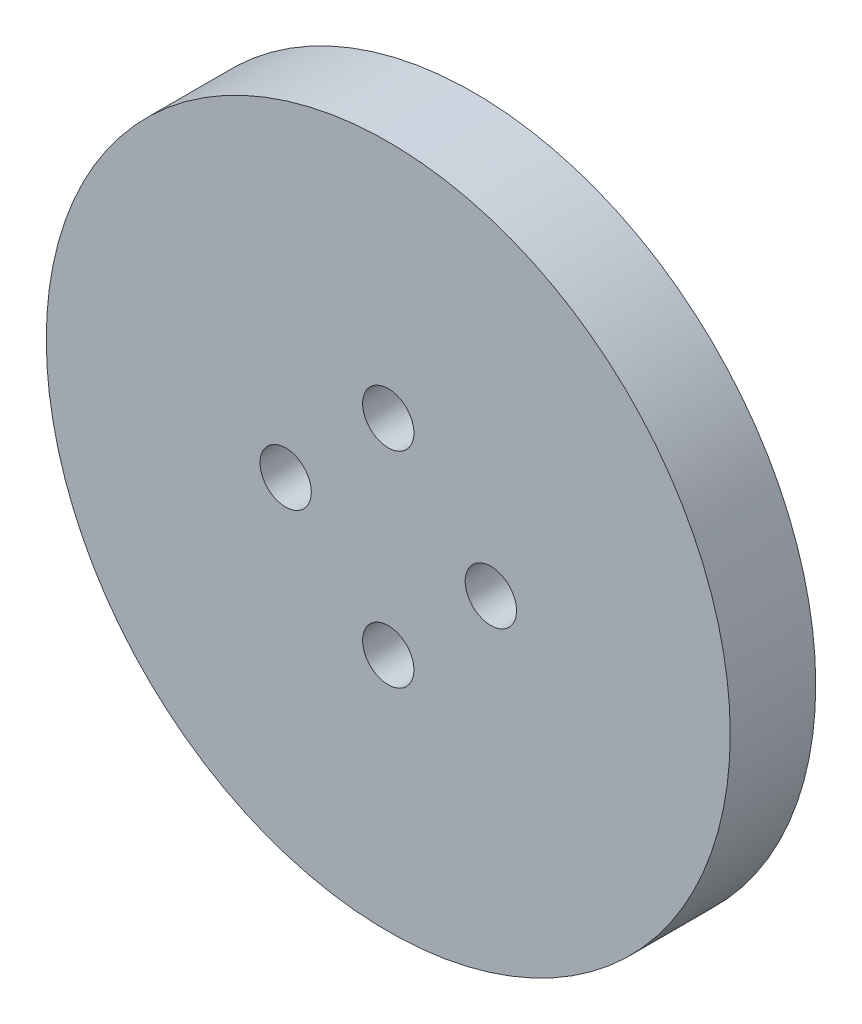
SolidWorks part; units mm, degrees
ref_plane "前视基准面" through (0, 0, 0) normal (0, 0, 1) x (1, 0, 0)
ref_plane "上视基准面" through (0, 0, 0) normal (0, 1, 0) x (1, 0, 0)
ref_plane "右视基准面" through (0, 0, 0) normal (1, 0, 0) x (0, 0, -1)
sketch "草图1" plane through (0, 0, 0) normal (0, 0, 1) x (1, 0, 0)
  circle A0 centre (0, 0) radius 17.5
  circle A1 centre (0, 0) radius 12
  circle A2 centre (-12, 0) radius 3
  circle A3 centre (0, 12) radius 3
  circle A4 centre (12, 0) radius 3
  circle A5 centre (0, -12) radius 3
  point P14 (0, 0)
  dimension "D1" = 35
  dimension "D2" = 24
  dimension "D3" = 4
extrude "凸台-拉伸1" add sketch "草图1" along normal blind 10 contours A0 A5 A1 A2 A3 A4 | A5 A1 A4 A3 A2
sketch "草图2" plane through (0, 0, 10) normal (0, 0, 1) x (1, 0, 0)
  circle A0 centre (0, 0) radius 40
  circle A1 centre (0, 0) radius 17.5
  circle M6 centre (0, 0) radius 17.5
extrude "凸台-拉伸3" add sketch "草图2" against normal blind 10 contours A0 M6
